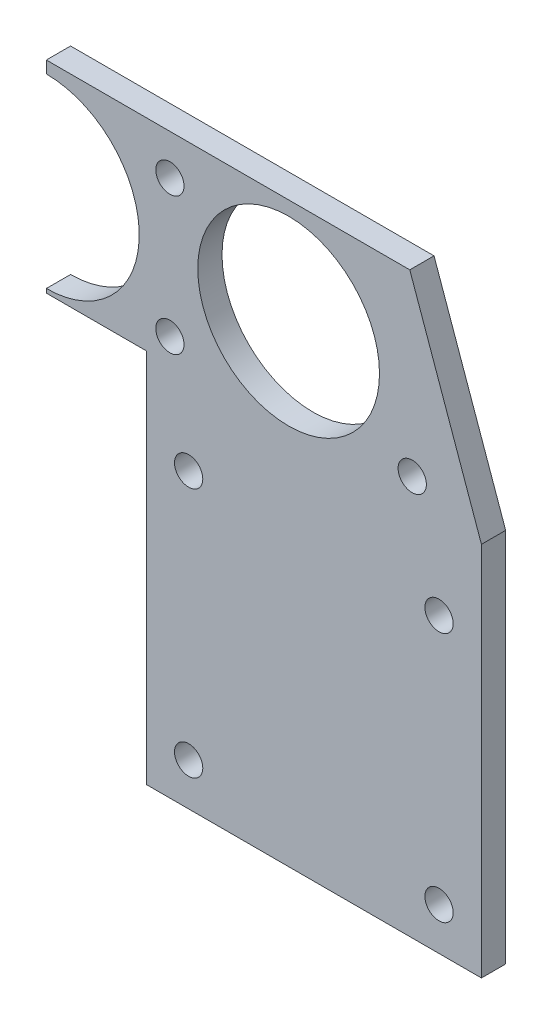
SolidWorks part; units mm, degrees
ref_plane "Front Plane" through (0, 0, 0) normal (0, 0, 1) x (1, 0, 0)
ref_plane "Top Plane" through (0, 0, 0) normal (0, 1, 0) x (1, 0, 0)
ref_plane "Right Plane" through (0, 0, 0) normal (1, 0, 0) x (0, 0, -1)
sketch "Sketch1" plane through (0, 0, 0) normal (0, 0, 1) x (1, 0, 0)
  line L19 (-125.663, -15.6875) -> (-84.163, -15.6875)
  line L20 (-125.663, 25.8125) -> (-125.663, -15.6875)
  line L22 (-78.0334, 25.8125) -> (-248.0334, 25.8125) construction
  line L29 (-84.163, 25.8125) -> (-84.163, -15.6875)
  line L37 (-84.163, 25.8125) -> (-84.163, 30.8125)
  line L38 (-84.163, 30.8125) -> (-191.9039, 30.8125) construction
  line L39 (-125.663, 25.8125) -> (-125.663, 30.8125)
  line L40 (-93.0334, 55.8125) -> (-84.163, 30.8125) construction
  line L41 (-84.163, 30.8125) -> (-93.0334, 55.8125)
  line L42 (-183.0334, 55.8125) -> (-93.0334, 55.8125) construction
  line L44 (-125.663, 30.8125) -> (-138.0334, 30.8125)
  line L45 (-138.0334, 55.8125) -> (-93.0334, 55.8125)
  line L46 (-138.0334, 55.8125) -> (-138.0334, 54.3125)
  line L47 (-138.0334, 31.3125) -> (-138.0334, 30.8125)
  circle A14 centre (-108.0334, 42.8125) radius 11.25
  circle A26 centre (-89.413, 20.5625) radius 1.75
  circle A27 centre (-120.413, 20.5625) radius 1.75
  circle A28 centre (-120.413, -10.4375) radius 1.75
  circle A29 centre (-89.413, -10.4375) radius 1.75
  circle A31 centre (-138.0334, 42.8125) radius 11.5 construction
  arc A32 (-138.0334, 31.3125) -> (-138.0334, 54.3125) centre (-138.0334, 42.8125) ccw
  circle A33 centre (-122.7334, 50.8125) radius 1.75
  circle A34 centre (-122.7334, 33.8125) radius 1.75
  circle A35 centre (-92.7334, 33.8125) radius 1.75
  dimension "D5" = 3.5
  dimension "D6" = 3.5
  dimension "D7" = 3.5
  dimension "D8" = 3.5
  dimension "D9" = 22.5
  dimension "D3" = 3.5
  dimension "D1" = 3.5
  dimension "D2" = 3.5
  dimension "D4" = 41.5
extrude "Boss-Extrude1" add sketch "Sketch1" along normal blind 3
